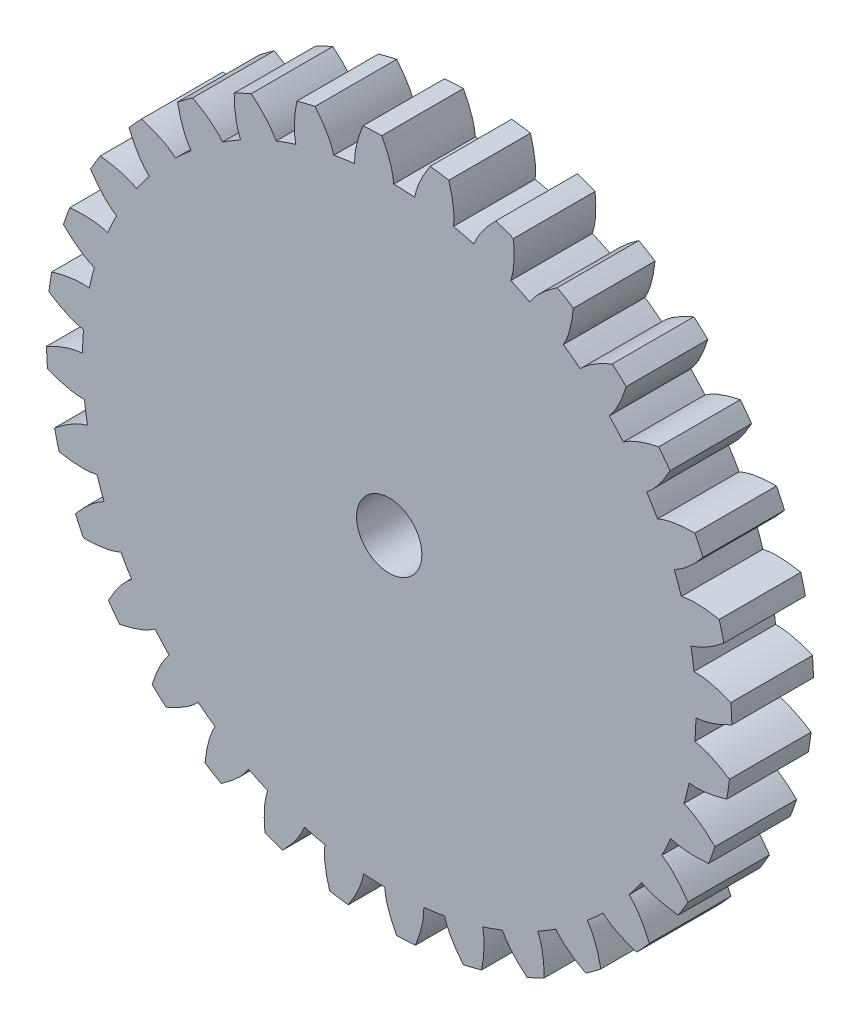
SolidWorks part; units mm, degrees
ref_plane "Front Plane" through (0, 0, 0) normal (0, 0, 1) x (1, 0, 0)
ref_plane "Top Plane" through (0, 0, 0) normal (0, 1, 0) x (1, 0, 0)
ref_plane "Right Plane" through (0, 0, 0) normal (1, 0, 0) x (0, 0, -1)
sketch "punti involuta" plane through (0, 0, 0) normal (0, 0, 1) x (1, 0, 0)
  line L0 (0, 0) -> (0, 4.6277) construction
  line L1 (-3.4916, 4) -> (3.4916, 4) construction
  line L2 (-3.4916, 2.7292) -> (3.4916, 5.2708) construction
  line L3 (0, 0) -> (-1.2856, 3.5321) construction
  line L4 (-1.2856, 3.5321) -> (0, 4) construction
  line L5 (-1.9173, 3.233) -> (-0.1385, 4.2879) construction
  line L6 (-0.9999, 3.6233) -> (0.0297, 3.9075) construction
  circle A0 centre (0, 0) radius 4 construction
  circle A1 centre (0, 0) radius 3.7588 construction
  arc A2 (-1.2856, 3.5321) -> (-1.9173, 3.233) centre (0, 0) ccw construction
  arc A3 (-1.2856, 3.5321) -> (-0.9999, 3.6233) centre (0, 0) cw construction
  arc A4 (-1.2856, 3.5321) -> (0.056, 3.7584) centre (0, 0) cw construction
  point P4 (0, 4)
  point P7 (0, 4)
  dimension "D1" = 8
  dimension "D2" = 20
  dimension "D3" = 1.3681
  dimension "D5" = 2.0681
  dimension "D7" = 1.0681
  dimension "D4" = 0.7
  dimension "D6" = 0.3
  dimension "D8" = 1.3681
sketch "diametro testa" plane through (0, 0, 0) normal (0, 0, 1) x (1, 0, 0)
  circle A0 centre (0, 0) radius 4.25
  dimension "D1" = 8.5
sketch "profilo" plane through (0, 0, 0) normal (0, 0, 1) x (1, 0, 0)
  line L0 (0, 0) -> (-0.1844, 3.7542) construction
  line L1 (0, 0) -> (0, 4.6277) construction
  line L2 (-0.1844, 3.7542) -> (-0.2085, 4.2449)
  arc A1 (-0.2085, 4.2449) -> (-0.1168, 4.2484) centre (0, 0) cw
  circle A3 centre (0, 0) radius 4.25 construction
  arc A4 (0.056, 3.7584) -> (-0.1844, 3.7542) centre (0, 0) ccw
  arc A5 (0.056, 3.7584) -> (-1.2856, 3.5321) centre (0, 0) ccw construction
  circle A6 centre (0, 0) radius 3.7588 construction
  spline S0 degree 3 poles (-0.1385, 4.2879) (-0.0478, 4.1243) (0.0412, 3.9487) (0.056, 3.7584) knots 0 0 0 0 1 1 1 1
  dimension "D1" = 2.813
sketch "diametro base" plane through (0, 0, 0) normal (0, 0, 1) x (1, 0, 0)
  circle A0 centre (0, 0) radius 3.7588
extrude "Boss-Extrude7" add sketch "profilo" along normal blind 1 contours S0 A1 L2 A4
ref_plane "Plane1" through (0, 0, 0) normal (0.9988, 0.0491, 0) x (-0.0491, 0.9988, 0)
mirror "Mirror1" about plane through (0, 0, 0) normal (0.9988, 0.0491, 0) of bodies 112
pattern_circular "CirPattern1" count 32 over 360 of bodies 113
extrude "Boss-Extrude9" add sketch "diametro base" along normal up to surface (1 mm away)
sketch "mozzo" plane through (0, 0, 0) normal (0, 0, 1) x (1, 0, 0)
  circle A0 centre (0, 0) radius 0.4
  dimension "D1" = 0.8
extrude "Cut-Extrude1" cut sketch "mozzo" along normal up to surface (1 mm away) up to face at (0, 0, 1)
sketch "Sketch1" plane through (0, 0, 1) normal (0, 0, 1) x (1, 0, 0)
  circle A0 centre (0, 0) radius 4.25 construction
  circle A1 centre (0, 0) radius 4.25
  circle A2 centre (0, 0) radius 4.2
  dimension "D1" = 0.05
extrude "Cut-Extrude2" cut sketch "Sketch1" against normal through all
equation "\"n_imposto\"= 32"
equation "\"m\"= .25"
equation "\"d_imposto\"= \"n_imposto\" * \"m\""
equation "\"alpha\"= 20"
equation "\"a1\"= .7"
equation "\"a2\"= .3"
equation "\"s\"= 1"
equation "\"D1@punti involuta\"=\"d_imposto\""
equation "\"D2@punti involuta\" = \"alpha\""
equation "\"D4@punti involuta\" = \"a1\""
equation "\"D5@punti involuta\" = \"D3@punti involuta\" + \"a1\""
equation "\"D6@punti involuta\" = \"a2\""
equation "\"D7@punti involuta\" = \"D3@punti involuta\" - \"a2\""
equation "\"D1@diametro testa\"=\"d_imposto\" + \"m\" * 2"
equation "\"D8@punti involuta\"=\"D3@punti involuta\""
equation "\"D1@profilo\"=360 / \"n_imposto\" / 4"
equation "\"D1@Boss-Extrude7\"=\"s\""
equation "\"D1@CirPattern1\"= \"n_imposto\""
equation "\"d_mozzo\"= .8"
equation "\"D1@mozzo\"=\"d_mozzo\""
